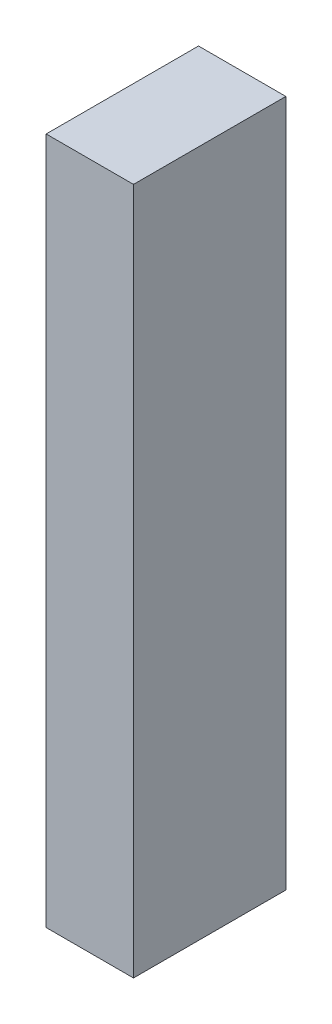
SolidWorks part; units mm, degrees
ref_plane "Přední rovina" through (0, 0, 0) normal (0, 0, 1) x (1, 0, 0)
ref_plane "Horní rovina" through (0, 0, 0) normal (0, 1, 0) x (1, 0, 0)
ref_plane "Pravá rovina" through (0, 0, 0) normal (1, 0, 0) x (0, 0, -1)
sketch "Skica1" plane through (0, 0, 0) normal (0, 0, 1) x (1, 0, 0)
  line L1 (2.465, 19.4) -> (-2.465, 19.4)
  line L2 (2.465, 19.4) -> (2.465, -19.4)
  line L3 (2.465, -19.4) -> (-2.465, -19.4)
  line L4 (-2.465, 19.4) -> (-2.465, -19.4)
  line L5 (2.465, 19.4) -> (-2.465, -19.4) construction
  line L6 (2.465, -19.4) -> (-2.465, 19.4) construction
  point P0 (0, 0)
  dimension "D1" = 38.8
  dimension "D2" = 4.93
extrude "Přidat vysunutím1" add sketch "Skica1" along normal blind 8.6
